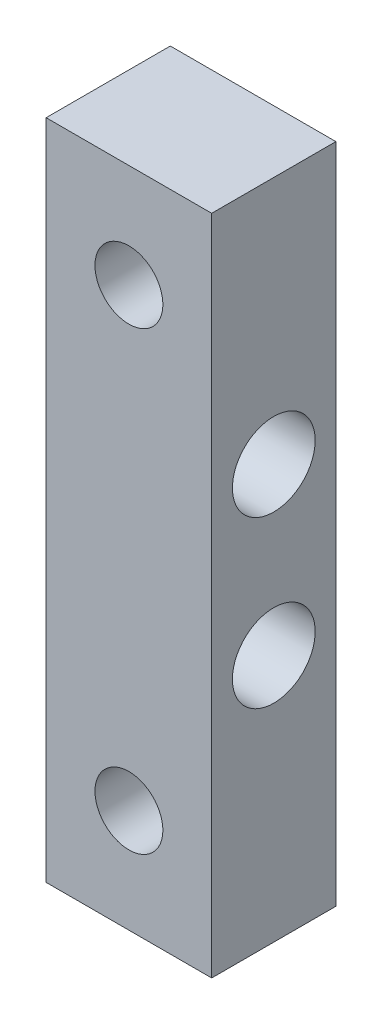
SolidWorks part; units mm, degrees
ref_plane "Front Plane" through (0, 0, 0) normal (0, 0, 1) x (1, 0, 0)
ref_plane "Top Plane" through (0, 0, 0) normal (0, 1, 0) x (1, 0, 0)
ref_plane "Right Plane" through (0, 0, 0) normal (1, 0, 0) x (0, 0, -1)
sketch "Sketch1" plane through (38.1, 0, 0) normal (1, 0, 0) x (0, 0, -1)
  line L0 (-152.4, 737.3561) -> (76.2, 737.3561) construction
  line L1 (-139.7, 788.1561) -> (-130.175, 788.1561)
  line L2 (-139.7, 788.1561) -> (-139.7, 737.3561)
  line L3 (-139.7, 737.3561) -> (-130.175, 737.3561)
  line L4 (-130.175, 788.1561) -> (-130.175, 737.3561)
  line L5 (-152.4, 788.1561) -> (76.2, 788.1561) construction
  line L6 (-152.4, 737.3561) -> (-152.4, 788.1561) construction
  line L7 (-139.7, 775.4561) -> (-130.175, 775.4561) construction
  line L8 (-139.7, 762.7561) -> (-130.175, 762.7561) construction
  line L9 (-139.7, 762.7561) -> (-130.175, 775.4561) construction
  line L10 (-139.7, 788.1561) -> (-130.175, 775.4561) construction
  circle A0 centre (-134.9375, 769.1061) radius 3.175
  circle A1 centre (-134.9375, 756.4061) radius 3.175
  dimension "D4" = 6.35
  dimension "D1" = 9.525
  dimension "D2" = 12.7
  dimension "D3" = 12.7
extrude "Boss-Extrude1" add sketch "Sketch1" along normal blind 12.7
sketch "Sketch2" plane through (0, 0, 130.175) normal (0, 0, -1) x (-1, 0, 0)
  circle A0 centre (-44.45, 780.2186) radius 3.175 construction
  circle A1 centre (-44.45, 745.2936) radius 3.175 construction
  circle A2 centre (-44.45, 780.2186) radius 3.175 construction
  circle A3 centre (-44.45, 745.2936) radius 3.175 construction
  circle A4 centre (-44.45, 780.2186) radius 2.6035
  circle A5 centre (-44.45, 745.2936) radius 2.6035
  dimension "D1" = 5.207
extrude "Cut-Extrude1" cut sketch "Sketch2" against normal up to next
